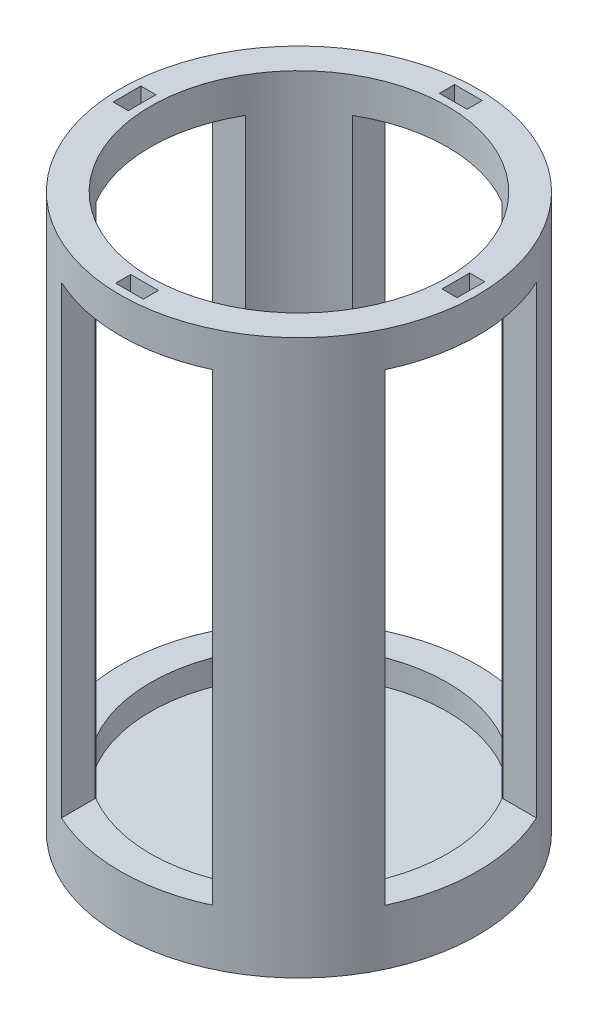
SolidWorks part; units mm, degrees
ref_plane "Front Plane" through (0, 0, 0) normal (0, 0, 1) x (1, 0, 0)
ref_plane "Top Plane" through (0, 0, 0) normal (0, 1, 0) x (1, 0, 0)
ref_plane "Right Plane" through (0, 0, 0) normal (1, 0, 0) x (0, 0, -1)
sketch "Sketch1" plane through (0, 0, 0) normal (0, 1, 0) x (1, 0, 0)
  circle A0 centre (0, 0) radius 45
  dimension "D1" = 90
extrude "Boss-Extrude3" add sketch "Sketch1" along normal blind 139.7
shell "Shell2" thickness 7.62
ref_plane "Plane1" through (45, 0, 0) normal (1, 0, 0) x (0, 0, -1)
sketch "Sketch15" plane through (45, 0, 0) normal (1, 0, 0) x (0, 0, -1)
  line L1 (-19.05, 130.81) -> (19.05, 130.81)
  line L2 (-19.05, 130.81) -> (-19.05, 13.97)
  line L3 (-19.05, 13.97) -> (19.05, 13.97)
  line L4 (19.05, 130.81) -> (19.05, 13.97)
  line L5 (-19.05, 130.81) -> (19.05, 13.97) construction
  line L6 (-19.05, 13.97) -> (19.05, 130.81) construction
  line L7 (37.38, 139.7) -> (-37.38, 139.7) construction
  point P0 (0, 72.39)
  dimension "D1" = 38.1
  dimension "D2" = 116.84
  dimension "D3" = 67.31
  dimension "D4" = 0
extrude "Cut-Extrude3" cut sketch "Sketch15" against normal blind 12.7
pattern_circular "CirPattern4" count 4 over 360 about axis through (0, 0, 0) along (0, 1, 0) of "Cut-Extrude3"
ref_plane "Plane4" through (0, 142.24, 0) normal (0, 1, 0) x (1, 0, 0)
sketch "Sketch14" plane through (0, 142.24, 0) normal (0, 1, 0) x (1, 0, 0)
  line L1 (-43.0116, 3.175) -> (-39.2016, 3.175)
  line L2 (-43.0116, 3.175) -> (-43.0116, -3.81)
  line L3 (-43.0116, -3.81) -> (-39.2016, -3.81)
  line L4 (-39.2016, 3.175) -> (-39.2016, -3.81)
  line L5 (-43.0116, 3.175) -> (-39.2016, -3.81) construction
  line L6 (-43.0116, -3.81) -> (-39.2016, 3.175) construction
  point P0 (-41.1066, -0.3175)
  dimension "D1" = 3.81
  dimension "D2" = 6.985
  dimension "D3" = 3.175
  dimension "D4" = 43.18
extrude "Cut-Extrude2" cut sketch "Sketch14" against normal blind 12.7
pattern_circular "CirPattern3" count 4 over 360 about axis through (0, 0, 0) along (0, 1, 0) of "Cut-Extrude2"
